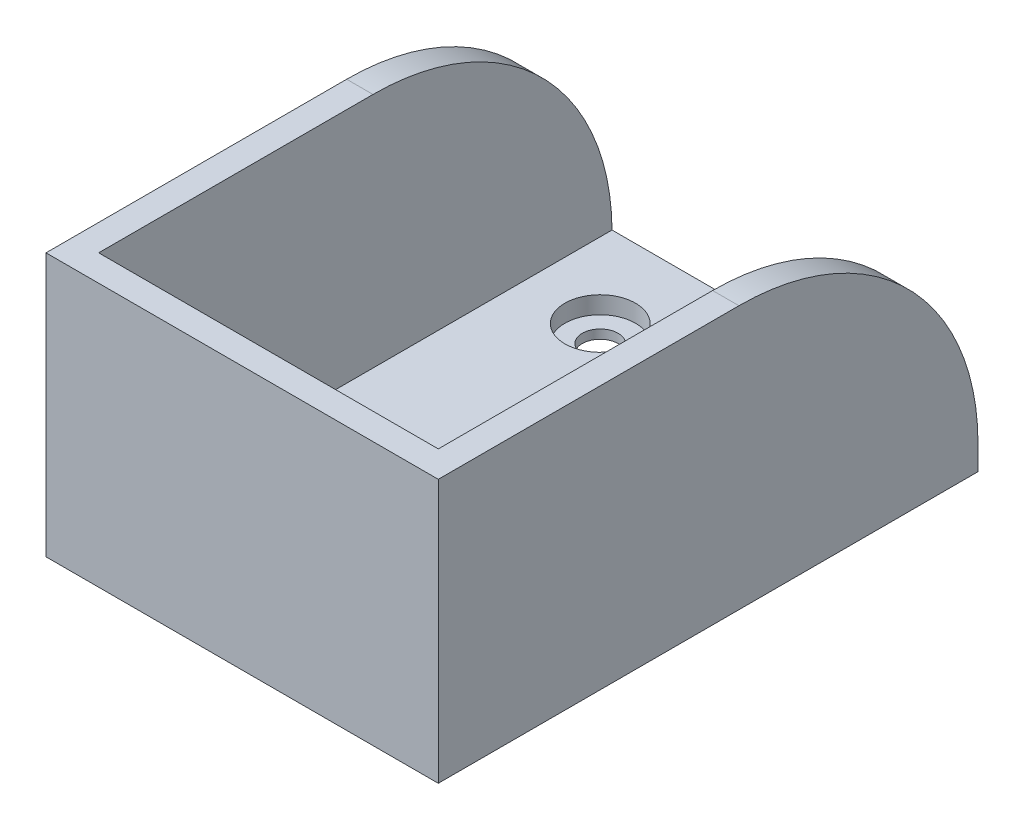
SolidWorks part; units mm, degrees
material "PBT General Purpose"
ref_plane "Front Plane" through (0, 0, 0) normal (0, 0, 1) x (1, 0, 0)
ref_plane "Top Plane" through (0, 0, 0) normal (0, 1, 0) x (1, 0, 0)
ref_plane "Right Plane" through (0, 0, 0) normal (1, 0, 0) x (0, 0, -1)
sketch "Sketch12" plane through (0, 0, 0) normal (0, 1, 0) x (1, 0, 0)
  line L1 (-16.125, -23.125) -> (16.125, -23.125)
  line L2 (-16.125, -23.125) -> (-16.125, 23.125)
  line L3 (-16.125, 23.125) -> (16.125, 23.125)
  line L4 (16.125, -23.125) -> (16.125, 23.125)
  line L5 (-16.125, -23.125) -> (16.125, 23.125) construction
  line L6 (-16.125, 23.125) -> (16.125, -23.125) construction
  point P0 (0, 0)
  dimension "D1" = 32.25
  dimension "D2" = 46.25
extrude "Boss-Extrude2" add sketch "Sketch12" along normal blind 2.5
sketch "Sketch13" plane through (0, 2.5, 0) normal (0, 1, 0) x (1, 0, 0)
  line L0 (0, 23.125) -> (0, -23.125) construction
  line L1 (-9, -18.125) -> (9, -18.125)
  line L2 (-9, -18.125) -> (-9, 14.875)
  line L3 (-9, 14.875) -> (9, 14.875)
  line L4 (9, -18.125) -> (9, 14.875)
  line L5 (-9, -18.125) -> (9, 14.875) construction
  line L6 (-9, 14.875) -> (9, -18.125) construction
  line L7 (16.125, 23.125) -> (-16.125, 23.125) construction
  line L8 (-16.125, -23.125) -> (16.125, -23.125) construction
  point P0 (0, -1.625)
  point P11 (0, -9.125)
  dimension "D1" = 33
  dimension "D2" = 18
  dimension "D3" = 5
  dimension "D4" = 14
hole_wizard "CBORE for M3 SBHCS1" positions "Sketch14" profile "Sketch15" counterbore size "M3" standard "ANSI Metric" end condition through all
sketch "Sketch14" plane through (0, 2.5, 0) normal (0, 1, 0) x (1, 0, 0)
  point P0 (-9, 14.875)
  point P3 (9, 14.875)
  point P6 (9, -18.125)
  point P9 (-9, -18.125)
sketch "Sketch15" plane through (-9, 2.5, -14.875) normal (1, 0, 0) x (0, 0, 1)
  line L0 (0, 0) -> (0, 2.5)
  line L1 (0, 2.5) -> (1.7, 2.5)
  line L3 (1.7, 2.5) -> (1.7, 1.65)
  line L4 (1.7, 1.65) -> (3.35, 1.65)
  line L5 (3.35, 1.65) -> (3.35, 0)
  line L7 (3.35, 0) -> (0, 0)
  line L11 (0, -6.35) -> (0, 107.95) construction
  dimension "Thru Hole Dia." = 3.4
  dimension "Thru Hole Depth" = 2.5
  dimension "C'Bore Dia." = 6.7
  dimension "C'Bore Depth" = 1.65
hole_wizard "Ø6.0mm Dowel Hole1" positions "Sketch18" profile "Sketch19" hole size "Ø6.0" standard "ANSI Metric" end condition through all
sketch "Sketch18" plane through (0, 2.5, 0) normal (0, 1, 0) x (1, 0, 0)
  point P0 (0, -9.125)
sketch "Sketch19" plane through (0, 2.5, 9.125) normal (1, 0, 0) x (0, 0, 1)
  line L0 (0, 0) -> (0, 2.5)
  line L1 (0, 2.5) -> (3.125, 2.5)
  line L2 (3.125, 2.5) -> (3.125, 0)
  line L5 (3.125, 0) -> (0, 0)
  line L11 (0, -6.35) -> (0, 107.95) construction
  dimension "Thru Hole Dia." = 6.25
  dimension "Thru Hole Depth" = 2.5
sketch "Sketch20" plane through (-16.125, 0, 0) normal (-1, 0, 0) x (0, 0, 1)
  line L0 (-23.125, 0) -> (23.125, 0) construction
  line L1 (23.125, 0) -> (-23.125, 0)
  line L2 (23.125, 0) -> (23.125, 25)
  line L3 (23.125, 25) -> (-23.125, 25)
  line L4 (-23.125, 0) -> (-23.125, 25)
  line L5 (-23.125, 2.5) -> (-23.125, 0) construction
  line L6 (23.125, 2.5) -> (23.125, 0) construction
  dimension "D1" = 25
ref_plane "Plane1" through (0, 0, 0) normal (-1, 0, 0) x (0, 0, 1)
extrude "Boss-Extrude3" add sketch "Sketch20" along normal blind 2.5 contours L4 L3 L2 L1
mirror "Mirror1" about plane through (0, 0, 0) normal (-1, 0, 0) of "Boss-Extrude3"
fillet "Fillet1" radius 22.7 1 edges at (-17.375, 25, -23.125)
sketch "Sketch22" plane through (0, 0, 23.125) normal (0, 0, 1) x (1, 0, 0)
  line L8 (-18.625, 0) -> (18.625, 0)
  line L9 (18.625, 0) -> (18.625, 25)
  line L10 (18.625, 25) -> (16.125, 25)
  line L11 (16.125, 25) -> (16.125, 2.5)
  line L12 (16.125, 2.5) -> (-16.125, 2.5)
  line L13 (-16.125, 2.5) -> (-16.125, 25)
  line L14 (-16.125, 25) -> (-18.625, 25)
  line L15 (-18.625, 25) -> (-18.625, 0)
  line L16 (-18.625, 0) -> (18.625, 0)
  line L17 (18.625, 0) -> (18.625, 25)
  line L18 (18.625, 25) -> (16.125, 25)
  line L19 (16.125, 25) -> (16.125, 2.5)
  line L20 (16.125, 2.5) -> (-16.125, 2.5)
  line L21 (-16.125, 2.5) -> (-16.125, 25)
  line L22 (-16.125, 25) -> (-18.625, 25)
  line L23 (-18.625, 25) -> (-18.625, 0)
  dimension "D1" = 0
extrude "Boss-Extrude4" add sketch "Sketch22" along normal blind 2.5
sketch "Sketch23" plane through (0, 0, 25.625) normal (0, 0, 1) x (1, 0, 0)
  line L1 (-18.625, 25) -> (18.625, 25)
  line L2 (-18.625, 25) -> (-18.625, 0)
  line L3 (-18.625, 0) -> (18.625, 0)
  line L4 (18.625, 25) -> (18.625, 0)
extrude "Boss-Extrude5" add sketch "Sketch23" along normal blind 2.5
